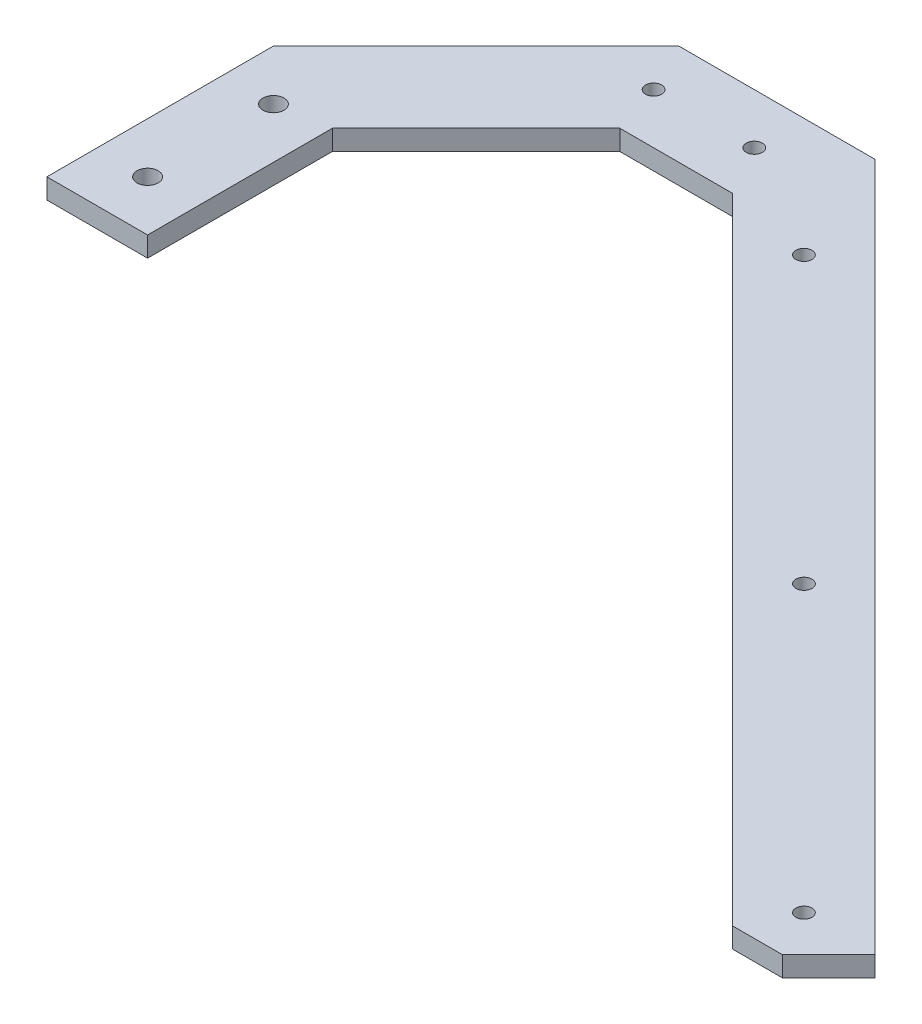
SolidWorks part; units mm, degrees
ref_plane "前视基准面" through (0, 0, 0) normal (0, 0, 1) x (1, 0, 0)
ref_plane "上视基准面" through (0, 0, 0) normal (0, 1, 0) x (1, 0, 0)
ref_plane "右视基准面" through (0, 0, 0) normal (1, 0, 0) x (0, 0, -1)
sketch "草图1" plane through (0, 0, 0) normal (0, 1, 0) x (1, 0, 0)
  line L0 (0, 22.5) -> (20, 22.5) construction
  line L2 (20, 0) -> (0, 0)
  line L3 (0, 0) -> (0, 45)
  line L4 (0, 45) -> (40.25, 85.25)
  line L8 (48.5343, 65.25) -> (20, 36.7157)
  line L10 (10, 22.5) -> (10, 0) construction
  line L12 (0, 0) -> (0, -140) construction
  line L13 (138.1079, -1.8921) -> (152.25, 12.25) construction
  line L14 (48.5343, 65.25) -> (70.9657, 65.25)
  line L22 (0, -140) -> (138.1079, -1.8921) construction
  line L27 (20, 36.7157) -> (20, 0)
  line L32 (59.75, 85.25) -> (59.75, 65.25) construction
  line L33 (59.75, 75.25) -> (30.25, 75.25) construction
  line L34 (20, -455) -> (20, 45) construction
  line L35 (40.25, 85.25) -> (0, 45) construction
  line L36 (40.25, 85.25) -> (79.25, 85.25)
  line L37 (79.25, 85.25) -> (225.25, -60.75)
  line L39 (215.25, -80.25) -> (215.25, -109.75) construction
  line L40 (225.25, -80.25) -> (205.25, -80.25) construction
  line L41 (162.5, -130) -> (140, -130) construction
  line L42 (70.9657, 65.25) -> (205.25, -69.0343)
  line L43 (162.5, -140) -> (162.5, -120) construction
  line L46 (225.25, -99.75) -> (225.25, -60.75)
  line L47 (176.7157, -120) -> (140, -120)
  line L48 (205.25, -91.4657) -> (205.25, -69.0343)
  line L49 (205.25, -91.4657) -> (176.7157, -120)
  line L50 (185, -140) -> (225.25, -99.75)
  line L51 (140, -140) -> (185, -140)
  line L52 (140, -120) -> (140, -140)
  circle A0 centre (10, 10) radius 2.1
  circle A1 centre (10, 35) radius 2.1
  circle A2 centre (175, -130) radius 2.1
  circle A3 centre (150, -130) radius 2.1
  dimension "D4" = 4.2
  dimension "D5" = 25
  dimension "D6" = 45
  dimension "D12" = 140
  dimension "D13" = 45
  dimension "D1" = 10
  dimension "D2" = 20
  dimension "D3" = 45
  dimension "D7" = 20
  dimension "D9" = 20
  dimension "D10" = 20
  dimension "D11" = 195.314
  dimension "D14" = 65.25
extrude "凸台-拉伸1" add sketch "草图1" along normal blind 4
sketch "草图2" plane through (0, 4, 0) normal (0, 1, 0) x (1, 0, 0)
  line L1 (225.25, -60.75) -> (225.25, -99.75)
  line L2 (225.25, -99.75) -> (185, -140)
  line L3 (185, -140) -> (140, -140)
  line L4 (140, -140) -> (140, -120)
  line L5 (140, -120) -> (140, -140) construction
  line L6 (140, -120) -> (176.7157, -120)
  line L7 (176.7157, -120) -> (205.25, -91.4657)
  line L8 (205.25, -91.4657) -> (205.25, -69.0343)
  line L11 (196.9657, -60.75) -> (205.25, -69.0343)
  line L13 (225.25, -60.75) -> (79.25, 85.25) construction
  line L15 (74.4683, 61.7475) -> (201.7475, -65.5317) construction
  line L16 (225.25, -99.75) -> (225.25, -60.75) construction
  line L17 (225.25, -60.75) -> (225.25, -99.75) construction
  line L18 (138.1079, -1.8921) -> (152.25, 12.25) construction
  line L19 (70.9657, 65.25) -> (205.25, -69.0343) construction
  line L20 (225.25, -60.75) -> (196.9657, -60.75)
extrude "切除-拉伸1" cut sketch "草图2" against normal blind 10
sketch "草图3" plane through (0, 4, 0) normal (0, 1, 0) x (1, 0, 0)
  line L0 (152.25, 12.25) -> (138.1079, -1.8921) construction
  line L1 (225.25, -60.75) -> (79.25, 85.25) construction
  line L2 (70.9657, 65.25) -> (196.9657, -60.75) construction
  line L3 (145.1789, 5.1789) -> (201.7475, -51.3896) construction
  line L4 (145.1789, 5.1789) -> (88.6104, 61.7475) construction
  circle A0 centre (201.7475, -51.3896) radius 1.6
  circle A1 centre (88.6104, 61.7475) radius 1.6
  circle A2 centre (145.1789, 5.1789) radius 1.6
  dimension "D1" = 3.2
  dimension "D2" = 80
extrude "切除-拉伸2" cut sketch "草图3" against normal blind 50
sketch "草图4" plane through (0, 4, 0) normal (0, 1, 0) x (1, 0, 0)
  line L0 (225.25, -60.75) -> (216.0576, -51.5576)
  line L1 (225.25, -60.75) -> (79.25, 85.25) construction
  line L2 (216.0576, -51.5576) -> (206.8652, -60.75)
  line L3 (225.25, -60.75) -> (196.9657, -60.75) construction
  line L4 (206.8652, -60.75) -> (225.25, -60.75)
  dimension "D1" = 13
extrude "切除-拉伸3" cut sketch "草图4" against normal blind 50
sketch "草图5" plane through (0, 4, 0) normal (0, 1, 0) x (1, 0, 0)
  line L0 (48.5343, 65.25) -> (48.5343, 85.25) construction
  line L1 (79.25, 85.25) -> (40.25, 85.25) construction
  line L2 (40.25, 85.25) -> (40.25, 56.9657) construction
  line L3 (20, 36.7157) -> (48.5343, 65.25) construction
  line L4 (65.25, 85.25) -> (65.25, 65.25) construction
  line L5 (48.5343, 65.25) -> (70.9657, 65.25) construction
  line L6 (65.25, 75.25) -> (45.25, 75.25) construction
  circle A0 centre (65.25, 75.25) radius 1.6
  circle A1 centre (45.25, 75.25) radius 1.6
  dimension "D2" = 3.2
  dimension "D1" = 20
  dimension "D3" = 5
extrude "切除-拉伸4" cut sketch "草图5" against normal blind 50
